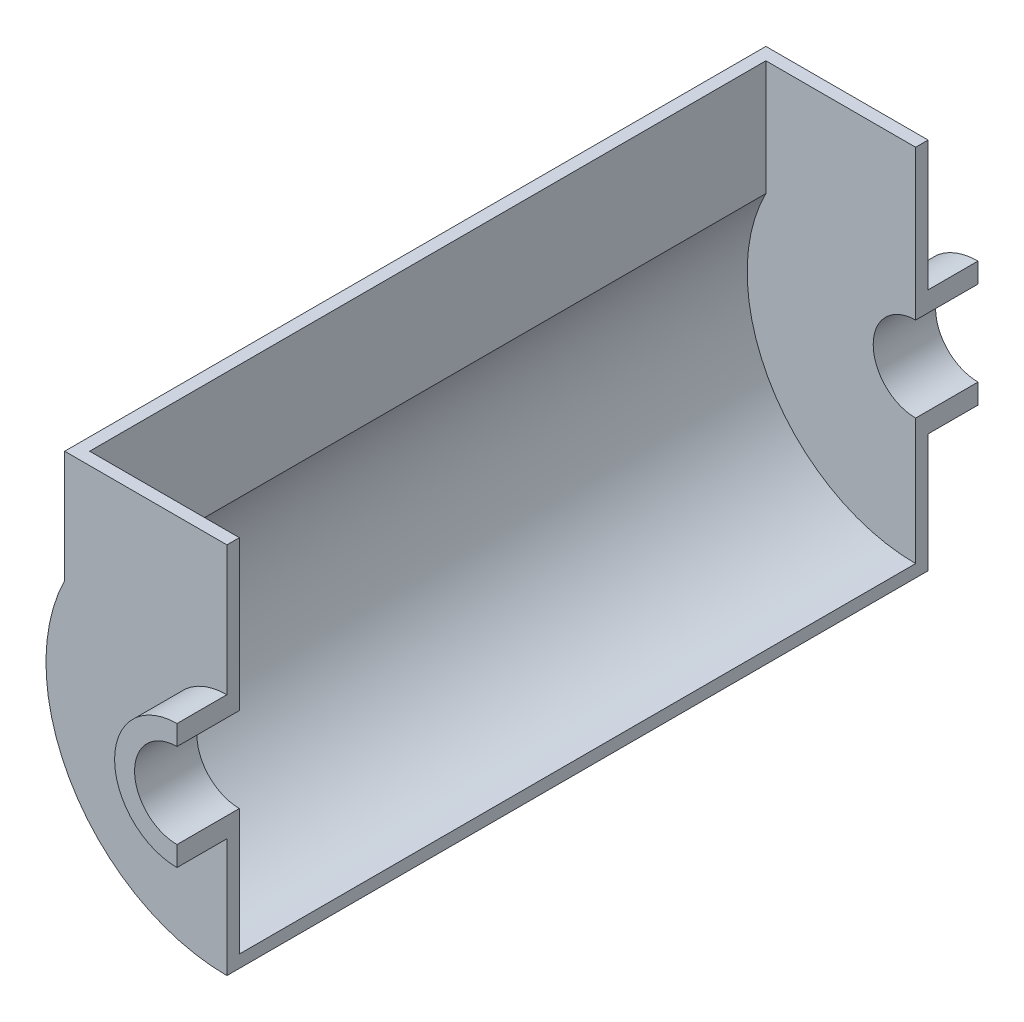
SolidWorks part; units mm, degrees
ref_plane "Front Plane" through (0, 0, 0) normal (0, 0, 1) x (1, 0, 0)
ref_plane "Top Plane" through (0, 0, 0) normal (0, 1, 0) x (1, 0, 0)
ref_plane "Right Plane" through (0, 0, 0) normal (1, 0, 0) x (0, 0, -1)
sketch "Sketch1" plane through (0, 0, 0) normal (0, 0, 1) x (1, 0, 0)
  line L0 (0, 25) -> (0, 17)
  line L1 (0, -17) -> (0, -25)
  arc A0 (0, 17) -> (0, -17) centre (0, 0) ccw
  arc A1 (0, 25) -> (0, -25) centre (0, 0) ccw
  dimension "D1" = 50
  dimension "D2" = 34
extrude "Boss-Extrude1" add sketch "Sketch1" along normal blind 20 and the other way blind 5
sketch "Sketch2" plane through (0, 0, 0) normal (0, 0, 1) x (1, 0, 0)
  line L0 (0, 25) -> (0, 77)
  line L1 (0, 77) -> (-65, 77)
  line L2 (-65, 77) -> (-65, 32.1131)
  line L3 (0, -25) -> (0, -72.5)
  arc A0 (0, 25) -> (0, -25) centre (0, 0) ccw construction
  arc A1 (0, 25) -> (0, -25) centre (0, 0) ccw
  arc A2 (-65, 32.1131) -> (0, -72.5) centre (0, 0) ccw
  dimension "D3" = 72.5
  dimension "D1" = 52
  dimension "D2" = 65
extrude "Boss-Extrude2" add sketch "Sketch2" against normal blind 5
ref_plane "Plane1" through (0, 0, -140.5) normal (0, 0, 1) x (1, 0, 0)
mirror "Mirror13" about plane through (0, 0, -140.5) normal (0, 0, 1) of bodies 102
sketch "Sketch3" plane through (0, 0, -5) normal (0, 0, -1) x (-1, 0, 0)
  line L0 (65, 77) -> (65, 32.1131) construction
  line L1 (65, 77) -> (65, 32.1131)
  line L2 (60, 77) -> (60, 30.9233)
  line L3 (0, -72.5) -> (0, -67.5)
  line L4 (65, 77) -> (60, 77)
  arc A0 (0, -72.5) -> (65, 32.1131) centre (0, 0) ccw construction
  arc A1 (0, -72.5) -> (65, 32.1131) centre (0, 0) ccw
  arc A2 (0, -67.5) -> (60, 30.9233) centre (0, 0) ccw
  dimension "D1" = 5
extrude "Boss-Extrude3" add sketch "Sketch3" along normal up to surface (271 mm away)
